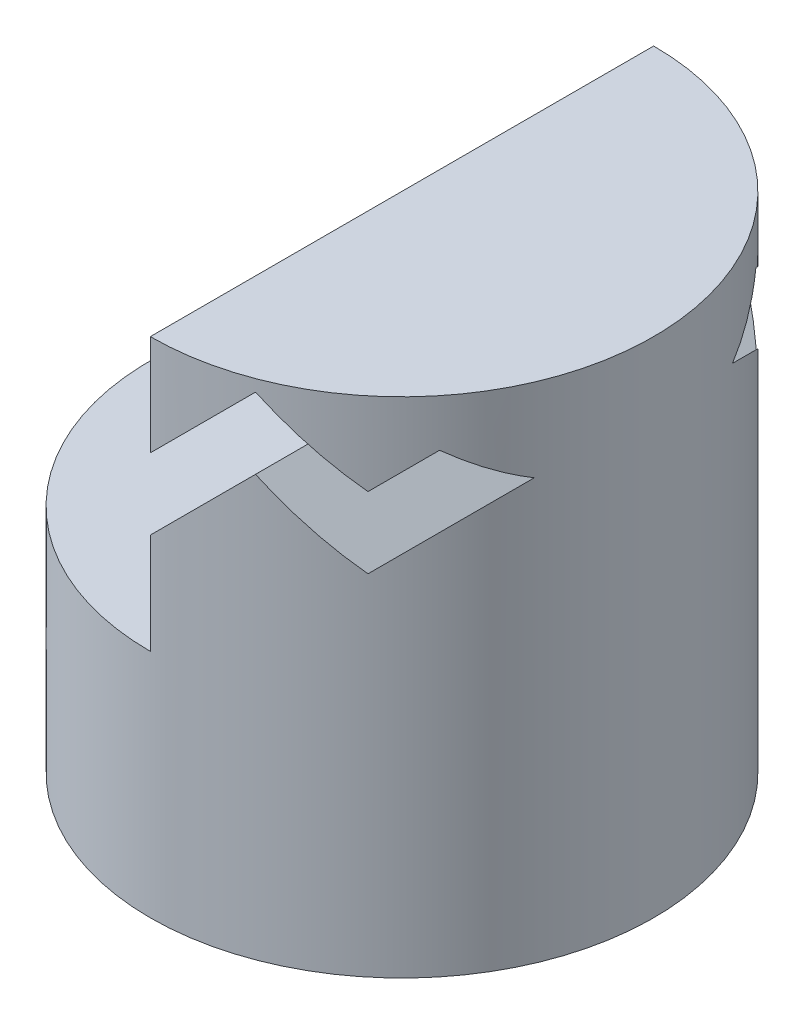
SolidWorks part; units mm, degrees
ref_plane "前视基准面" through (0, 0, 0) normal (0, 0, 1) x (1, 0, 0)
ref_plane "上视基准面" through (0, 0, 0) normal (0, 1, 0) x (1, 0, 0)
ref_plane "右视基准面" through (0, 0, 0) normal (1, 0, 0) x (0, 0, -1)
sketch "草图1" plane through (0, 0, 0) normal (0, 1, 0) x (1, 0, 0)
  circle A0 centre (0, 0) radius 50
  dimension "D1" = 100
extrude "凸台-拉伸1" add sketch "草图1" along normal blind 100
sketch "草图2" plane through (0, 0, 0) normal (0, 0, 1) x (1, 0, 0)
  line L0 (0, 100) -> (0, 80)
  line L1 (50, 100) -> (-50, 100) construction
  line L4 (17.6777, 83.5355) -> (0, 65.8579)
  line L5 (0, 65.8579) -> (0, 45.8579)
  line L6 (0, 45.8579) -> (-50, 45.8579)
  line L7 (-50, 100) -> (-50, 0) construction
  line L8 (-50, 45.8579) -> (-50, 100)
  line L9 (-50, 100) -> (0, 100)
  line L10 (17.6777, 83.5355) -> (31.8198, 69.3934)
  line L11 (31.8198, 69.3934) -> (45.9619, 83.5355)
  line L12 (45.9619, 83.5355) -> (38.8909, 90.6066)
  line L13 (38.8909, 90.6066) -> (31.8198, 83.5355)
  line L14 (31.8198, 83.5355) -> (17.6777, 97.6777)
  line L16 (0, 80) -> (17.6777, 97.6777)
  dimension "D1" = 20
  dimension "D2" = 20
  dimension "D3" = 25
  dimension "D4" = 10
  dimension "D5" = 10
  dimension "D6" = 20
  dimension "D7" = 10
extrude "切除-拉伸1" cut sketch "草图2" against normal through all both and the other way through all
